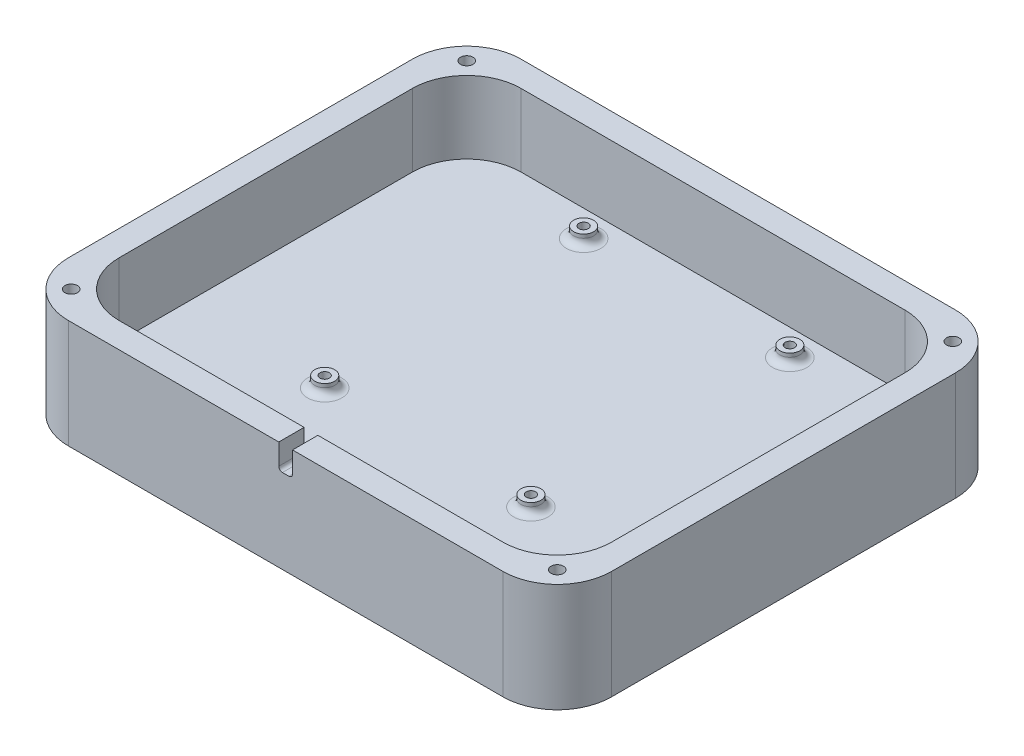
SolidWorks part; units mm, degrees
ref_plane "Front Plane" through (0, 0, 0) normal (0, 0, 1) x (1, 0, 0)
ref_plane "Top Plane" through (0, 0, 0) normal (0, 1, 0) x (1, 0, 0)
ref_plane "Right Plane" through (0, 0, 0) normal (1, 0, 0) x (0, 0, -1)
sketch "Sketch1" plane through (0, 0, 0) normal (0, 1, 0) x (1, 0, 0)
  line L1 (-75, 50) -> (75, 50)
  line L2 (-75, 50) -> (-75, -50)
  line L3 (-75, -50) -> (75, -50)
  line L4 (75, 50) -> (75, -50)
  line L5 (-75, 50) -> (75, -50) construction
  line L6 (-75, -50) -> (75, 50) construction
  point P0 (0, 0)
  dimension "D1" = 150
  dimension "D2" = 100
extrude "Boss-Extrude1" add sketch "Sketch1" along normal blind 10
sketch "Sketch2" plane through (0, 10, 0) normal (0, 1, 0) x (1, 0, 0)
  line L0 (75, -50) -> (75, 50) construction
  line L1 (0, 0) -> (0, 70.2566) construction
  line L2 (75, 50) -> (-75, 50) construction
  line L3 (0, 0) -> (146.4068, 0) construction
  circle A1 centre (28.47, 35.745) radius 2.75
  circle A2 centre (28.47, -35.745) radius 2.75
  circle A3 centre (-28.47, -35.745) radius 2.75
  circle A4 centre (-28.47, 35.745) radius 2.75
  point P0 (28.47, 35.745)
  point P8 (-28.47, -35.745)
  point P9 (28.47, -35.745)
  point P16 (-28.47, 35.745)
  dimension "D5" = 5.5
  dimension "D1" = 46.53
  dimension "D2" = 14.255
extrude "Boss-Extrude2" add sketch "Sketch2" along normal blind 3
hole_wizard "Ø1.0mm Dowel Hole1" positions "Sketch3" profile "Sketch4" hole size "Ø1.0" standard "ISO"
sketch "Sketch3" plane through (0, 13, 0) normal (0, 1, 0) x (1, 0, 0)
  point P0 (-28.47, 35.745)
  point P3 (28.47, 35.745)
  point P6 (28.47, -35.745)
  point P9 (-28.47, -35.745)
sketch "Sketch4" plane through (-28.47, 13, -35.745) normal (1, 0, 0) x (0, 0, 1)
  line L0 (0, 0) -> (0, 10.7811)
  line L1 (0, 10.7811) -> (1.3, 10)
  line L2 (1.3, 10) -> (1.3, 0)
  line L5 (1.3, 0) -> (0, 0)
  line L10 (0, 10.7811) -> (-1.3, 10) construction
  line L11 (0, -6.35) -> (0, 107.95) construction
  dimension "Hole Dia." = 2.6
  dimension "Hole Depth" = 10
  dimension "Drill Angle" = 118
fillet "Fillet1" radius 2 4 edges at (28.47, 10, 32.995) (-28.47, 10, 38.495) (28.47, 10, -32.995) (-28.47, 10, -38.495)
sketch "Sketch5" plane through (0, 0, 0) normal (0, -1, 0) x (1, 0, 0)
  line L1 (-75, 50) -> (75, 50)
  line L2 (-75, 50) -> (-75, 75)
  line L3 (-75, 75) -> (75, 75)
  line L4 (75, 50) -> (75, 75)
  dimension "D1" = 25
extrude "Boss-Extrude3" add sketch "Sketch5" against normal blind 10
sketch "Sketch7" plane through (0, 10, 0) normal (0, 1, 0) x (1, 0, 0)
  line L1 (-75, 50) -> (75, 50)
  line L2 (-75, 50) -> (-75, -75)
  line L3 (-75, -75) -> (75, -75)
  line L4 (75, 50) -> (75, -75)
extrude "Extrude-Thin1" add sketch "Sketch7" along normal blind 20 thin
sketch "Sketch8" plane through (0, 0, 75) normal (0, 0, 1) x (1, 0, 0)
  line L0 (0, 30) -> (0, 23.2) construction
  line L1 (-75, 30) -> (75, 30) construction
  line L2 (-1.9, 30) -> (1.9, 30)
  line L3 (1.9, 30) -> (1.9, 24.2)
  line L4 (0.9, 23.2) -> (-0.9, 23.2)
  line L5 (-1.9, 30) -> (-1.9, 24.2)
  arc A0 (1.9, 24.2) -> (0.9, 23.2) centre (0.9, 24.2) cw
  arc A1 (-1.9, 24.2) -> (-0.9, 23.2) centre (-0.9, 24.2) ccw
  dimension "D2" = 1
  dimension "D1" = 1.9
  dimension "D3" = 5.8
extrude "Cut-Extrude1" cut sketch "Sketch8" against normal up to next
fillet "Fillet2" radius 15 4 edges at (75, 15, 75) (75, 15, -50) (-75, 15, -50) (-75, 15, 75)
fillet "Fillet3" radius 15 4 edges at (-68, 20, -43) (-68, 20, 68) (68, 20, -43) (68, 20, 68)
sketch "Sketch9" plane through (0, 30, 0) normal (0, 1, 0) x (1, 0, 0)
  line L0 (-63.6066, 38.6066) -> (-70.6066, 45.6066) construction
  line L1 (-75, -12.5) -> (75, -12.5) construction
  line L2 (-75, 35) -> (-75, -60) construction
  line L3 (75, -60) -> (75, 35) construction
  line L4 (0, 50) -> (0, -75) construction
  line L5 (60, 50) -> (-60, 50) construction
  line L6 (-0.9, -75) -> (0.9, -75) construction
  arc A0 (-53, 43) -> (-68, 28) centre (-53, 28) ccw construction
  arc A1 (-60, 50) -> (-75, 35) centre (-60, 35) ccw construction
  circle A2 centre (-67.1066, 42.1066) radius 1.725
  circle A3 centre (67.1066, 42.1066) radius 1.725
  circle A4 centre (67.1066, -67.1066) radius 1.725
  circle A5 centre (-67.1066, -67.1066) radius 1.725
  dimension "D1" = 3.45
extrude "Cut-Extrude2" cut sketch "Sketch9" against normal blind 6
